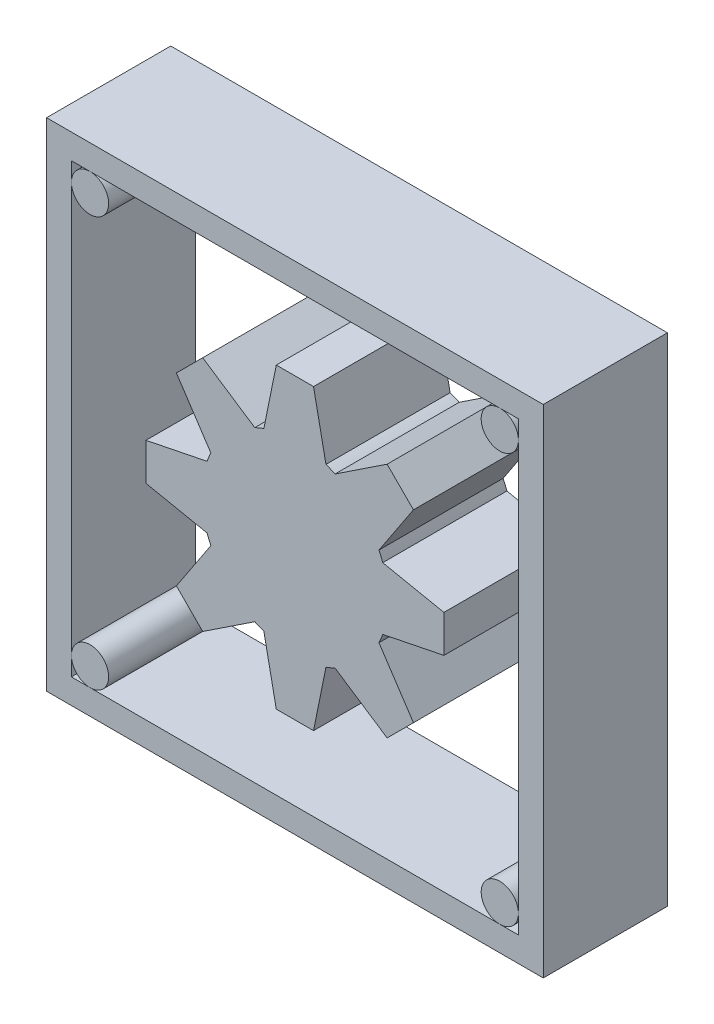
SolidWorks part; units mm, degrees
ref_plane "Front Plane" through (0, 0, 0) normal (0, 0, 1) x (1, 0, 0)
ref_plane "Top Plane" through (0, 0, 0) normal (0, 1, 0) x (1, 0, 0)
ref_plane "Right Plane" through (0, 0, 0) normal (1, 0, 0) x (0, 0, -1)
sketch "Sketch1" plane through (0, 0, 0) normal (0, 0, 1) x (1, 0, 0)
  line L0 (-2.5, 7.0711) -> (-1.5, 12)
  line L1 (-20, 20) -> (20, 20)
  line L2 (-20, 20) -> (-20, -20)
  line L3 (-20, -20) -> (20, -20)
  line L4 (20, 20) -> (20, -20)
  line L5 (-20, 20) -> (20, -20) construction
  line L6 (-20, -20) -> (20, 20) construction
  line L7 (-18, 18) -> (18, 18)
  line L8 (-18, 18) -> (-18, -18)
  line L9 (-18, -18) -> (18, -18)
  line L10 (18, 18) -> (18, -18)
  line L11 (-18, 18) -> (18, -18) construction
  line L12 (-18, -18) -> (18, 18) construction
  line L13 (-1.5, 12) -> (1.5, 12)
  line L14 (1.5, 12) -> (2.5, 7.0711)
  line L15 (3.2322, 6.7678) -> (7.4246, 9.5459)
  line L16 (7.4246, 9.5459) -> (9.5459, 7.4246)
  line L17 (9.5459, 7.4246) -> (6.7678, 3.2322)
  line L18 (7.0711, 2.5) -> (12, 1.5)
  line L19 (12, 1.5) -> (12, -1.5)
  line L20 (12, -1.5) -> (7.0711, -2.5)
  line L21 (6.7678, -3.2322) -> (9.5459, -7.4246)
  line L22 (9.5459, -7.4246) -> (7.4246, -9.5459)
  line L23 (7.4246, -9.5459) -> (3.2322, -6.7678)
  line L24 (2.5, -7.0711) -> (1.5, -12)
  line L25 (1.5, -12) -> (-1.5, -12)
  line L26 (-1.5, -12) -> (-2.5, -7.0711)
  line L27 (-3.2322, -6.7678) -> (-7.4246, -9.5459)
  line L28 (-7.4246, -9.5459) -> (-9.5459, -7.4246)
  line L29 (-9.5459, -7.4246) -> (-6.7678, -3.2322)
  line L30 (-7.0711, -2.5) -> (-12, -1.5)
  line L31 (-12, -1.5) -> (-12, 1.5)
  line L32 (-12, 1.5) -> (-7.0711, 2.5)
  line L33 (-6.7678, 3.2322) -> (-9.5459, 7.4246)
  line L34 (-9.5459, 7.4246) -> (-7.4246, 9.5459)
  line L35 (-7.4246, 9.5459) -> (-3.2322, 6.7678)
  arc A0 (2.5, -7.0711) -> (3.2322, -6.7678) centre (0, 0) ccw
  arc A1 (-7.0711, -2.5) -> (-6.7678, -3.2322) centre (0, 0) ccw
  arc A2 (-7.0711, -2.5) -> (-6.7678, -3.2322) centre (0, 0) ccw
  arc A3 (-7.0711, -2.5) -> (-6.7678, -3.2322) centre (0, 0) ccw
  arc A4 (-7.1723, -2.1928) -> (-6.7678, -3.2322) centre (0, 0) ccw
  arc A5 (-7.1723, -2.1928) -> (-6.7678, -3.2322) centre (0, 0) ccw
  arc A6 (-7.1723, -2.1928) -> (-6.7678, -3.2322) centre (0, 0) ccw
  arc A7 (-7.0711, -2.5) -> (-6.7678, -3.2322) centre (0, 0) ccw
  arc A8 (2.5, -7.0711) -> (3.2322, -6.7678) centre (0, 0) ccw
  arc A9 (2.5, -7.0711) -> (3.2322, -6.7678) centre (0, 0) ccw
  arc A10 (2.5, -7.0711) -> (3.2322, -6.7678) centre (0, 0) ccw
  arc A11 (2.5, -7.0711) -> (3.2322, -6.7678) centre (0, 0) ccw
  arc A12 (2.5, -7.0711) -> (3.2322, -6.7678) centre (0, 0) ccw
  arc A13 (2.5, -7.0711) -> (3.2322, -6.7678) centre (0, 0) ccw
  arc A14 (7.0711, 2.5) -> (6.7678, 3.2322) centre (0, 0) ccw
  arc A15 (7.0711, 2.5) -> (6.7678, 3.2322) centre (0, 0) ccw
  arc A16 (7.0711, 2.5) -> (6.7678, 3.2322) centre (0, 0) ccw
  arc A17 (7.0711, 2.5) -> (6.7678, 3.2322) centre (0, 0) ccw
  arc A18 (7.0711, 2.5) -> (6.7678, 3.2322) centre (0, 0) ccw
  arc A19 (7.0711, 2.5) -> (6.7678, 3.2322) centre (0, 0) ccw
  arc A20 (7.0711, 2.5) -> (6.7678, 3.2322) centre (0, 0) ccw
  arc A21 (3.2322, 6.7678) -> (2.5, 7.0711) centre (0, 0) ccw
  arc A22 (3.2322, 6.7678) -> (2.5, 7.0711) centre (0, 0) ccw
  arc A23 (3.2322, 6.7678) -> (2.5, 7.0711) centre (0, 0) ccw
  arc A24 (3.2322, 6.7678) -> (2.5, 7.0711) centre (0, 0) ccw
  arc A25 (3.2322, 6.7678) -> (2.5, 7.0711) centre (0, 0) ccw
  arc A26 (3.2322, 6.7678) -> (2.5, 7.0711) centre (0, 0) ccw
  arc A27 (3.2322, 6.7678) -> (2.5, 7.0711) centre (0, 0) ccw
  arc A28 (-2.5, 7.0711) -> (-3.2322, 6.7678) centre (0, 0) ccw
  arc A29 (-2.5, 7.0711) -> (-3.2322, 6.7678) centre (0, 0) ccw
  arc A30 (-2.5, 7.0711) -> (-3.2322, 6.7678) centre (0, 0) ccw
  arc A31 (-2.5, 7.0711) -> (-3.2322, 6.7678) centre (0, 0) ccw
  arc A32 (-2.5, 7.0711) -> (-3.2322, 6.7678) centre (0, 0) ccw
  arc A33 (-2.5, 7.0711) -> (-3.2322, 6.7678) centre (0, 0) ccw
  arc A34 (-2.5, 7.0711) -> (-3.2322, 6.7678) centre (0, 0) ccw
  arc A35 (-6.7678, 3.2322) -> (-7.0711, 2.5) centre (0, 0) ccw
  arc A36 (-6.7678, 3.2322) -> (-7.0711, 2.5) centre (0, 0) ccw
  arc A37 (-6.7678, 3.2322) -> (-7.0711, 2.5) centre (0, 0) ccw
  arc A38 (-6.7678, 3.2322) -> (-7.0711, 2.5) centre (0, 0) ccw
  arc A39 (-6.7678, 3.2322) -> (-7.0711, 2.5) centre (0, 0) ccw
  arc A40 (-6.7678, 3.2322) -> (-7.0711, 2.5) centre (0, 0) ccw
  arc A41 (-6.7678, 3.2322) -> (-7.0711, 2.5) centre (0, 0) ccw
  arc A42 (-3.2322, -6.7678) -> (-2.5, -7.0711) centre (0, 0) ccw
  arc A43 (-3.2322, -6.7678) -> (-2.5, -7.0711) centre (0, 0) ccw
  arc A44 (-3.2322, -6.7678) -> (-2.5, -7.0711) centre (0, 0) ccw
  arc A45 (-3.2322, -6.7678) -> (-2.5, -7.0711) centre (0, 0) ccw
  arc A46 (-3.2322, -6.7678) -> (-2.5, -7.0711) centre (0, 0) ccw
  arc A47 (-3.2322, -6.7678) -> (-2.5, -7.0711) centre (0, 0) ccw
  arc A48 (-3.2322, -6.7678) -> (-2.5, -7.0711) centre (0, 0) ccw
  arc A49 (6.7678, -3.2322) -> (7.0711, -2.5) centre (0, 0) ccw
  arc A50 (6.7678, -3.2322) -> (7.0711, -2.5) centre (0, 0) ccw
  arc A51 (6.7678, -3.2322) -> (7.0711, -2.5) centre (0, 0) ccw
  arc A52 (6.7678, -3.2322) -> (7.0711, -2.5) centre (0, 0) ccw
  arc A53 (6.7678, -3.2322) -> (7.0711, -2.5) centre (0, 0) ccw
  arc A54 (6.7678, -3.2322) -> (7.0711, -2.5) centre (0, 0) ccw
  arc A55 (6.7678, -3.2322) -> (7.0711, -2.5) centre (0, 0) ccw
  point P0 (0, 0)
  point P6 (0, 0)
  point P15 (0, 12)
  point P56 (0, 0)
  dimension "D1" = 40
  dimension "D2" = 40
  dimension "D3" = 2
  dimension "D5" = 12
  dimension "D6" = 3
  dimension "D7" = 5
  dimension "D8" = 8
extrude "Boss-Extrude1" add sketch "Sketch1" along normal blind 10
sketch "Sketch2" plane through (0, 0, 10) normal (0, 0, 1) x (1, 0, 0)
  line L0 (18, 18) -> (18, -18) construction
  line L1 (-18, 18) -> (18, 18) construction
  line L2 (-18, -18) -> (18, -18) construction
  line L3 (-18, 18) -> (-18, -18) construction
  circle A0 centre (-16.5, 16.5) radius 1.5
  circle A1 centre (16.5, 16.5) radius 1.5
  circle A2 centre (16.5, -16.5) radius 1.5
  circle A3 centre (-16.5, -16.5) radius 1.5
  dimension "D1" = 3
extrude "Boss-Extrude2" add sketch "Sketch2" against normal blind 10 separate body
